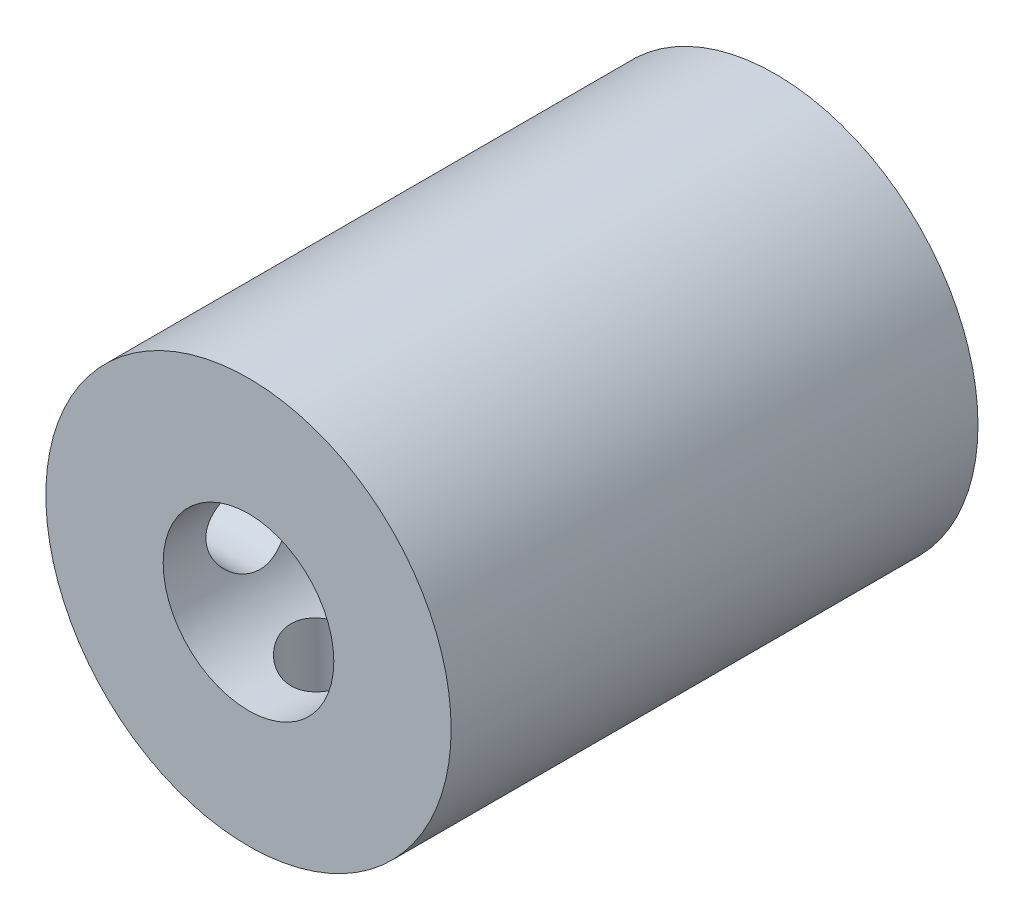
SolidWorks part; units mm, degrees
ref_plane "Plan de face" through (0, 0, 0) normal (0, 0, 1) x (1, 0, 0)
ref_plane "Plan de dessus" through (0, 0, 0) normal (0, 1, 0) x (1, 0, 0)
ref_plane "Plan de droite" through (0, 0, 0) normal (1, 0, 0) x (0, 0, -1)
sketch "Esquisse1" plane through (0, 0, 0) normal (0, 0, 1) x (1, 0, 0)
  circle A0 centre (0, 0) radius 9.5
  dimension "D1" = 19
extrude "Boss.-Extru.1" add sketch "Esquisse1" along normal blind 24.7
sketch "Esquisse2" plane through (0, 0, 24.7) normal (0, 0, 1) x (1, 0, 0)
  circle A0 centre (0, 0) radius 4
  dimension "D1" = 8
extrude "Enlèv. mat.-Extru.1" cut sketch "Esquisse2" against normal blind 18
sketch "Esquisse3" plane through (0, 0, 0) normal (0, 0, -1) x (-1, 0, 0)
  circle A0 centre (0, 0) radius 2.5
  dimension "D1" = 5
extrude "Enlèv. mat.-Extru.2" cut sketch "Esquisse3" against normal through all
sketch "Esquisse4" plane through (0, 0, 0) normal (0, 1, 0) x (1, 0, 0)
  line L0 (2.5, 0) -> (-2.5, 0) construction
  line L1 (-9.5, -24.7) -> (9.5, -24.7) construction
  circle A0 centre (0, -4) radius 2
  circle A1 centre (0, -20.7) radius 2
  point P9 (0, 0)
  dimension "D1" = 4
  dimension "D2" = 4
  dimension "D3" = 4
extrude "Enlèv. mat.-Extru.3" cut sketch "Esquisse4" against normal through all contours A0 | A1
pattern_circular "Répétition circulaire1" count 2 over 90 about axis through (0, 0, 6.7) along (0, 0, 1) of "Enlèv. mat.-Extru.3"
